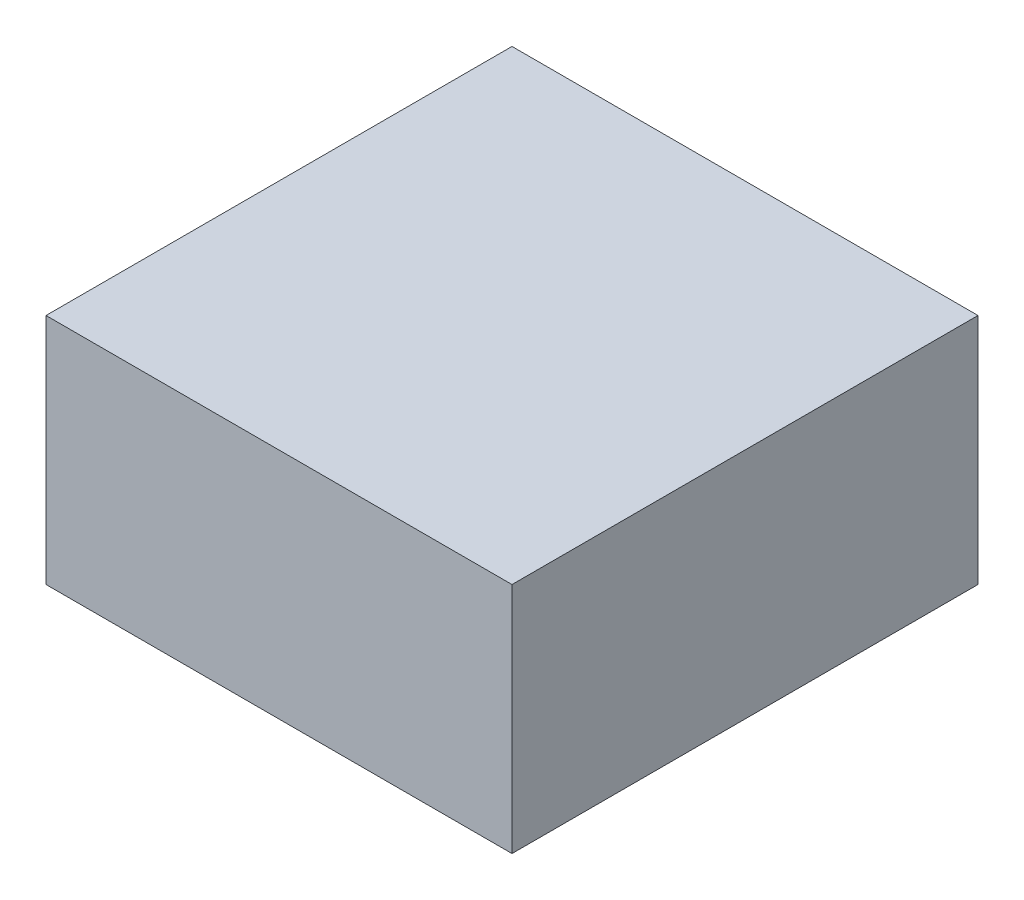
SolidWorks part; units mm, degrees
material "Beech"
ref_plane "Front Plane" through (0, 0, 0) normal (0, 0, 1) x (1, 0, 0)
ref_plane "Top Plane" through (0, 0, 0) normal (0, 1, 0) x (1, 0, 0)
ref_plane "Right Plane" through (0, 0, 0) normal (1, 0, 0) x (0, 0, -1)
sketch "Sketch1" plane through (0, 0, 0) normal (0, 1, 0) x (1, 0, 0)
  line L1 (0, 0) -> (304.8, 0)
  line L2 (0, 0) -> (0, 304.8)
  line L3 (0, 304.8) -> (304.8, 304.8)
  line L4 (304.8, 0) -> (304.8, 304.8)
  dimension "D1" = 304.8
  dimension "D2" = 304.8
extrude "Boss-Extrude1" add sketch "Sketch1" along normal blind 6.35
sketch "Sketch2" plane through (0, 6.35, 0) normal (0, 1, 0) x (1, 0, 0)
  line L1 (304.8, 304.8) -> (0, 304.8) construction
  line L2 (12.7, 304.8) -> (12.7, 292.1)
  line L3 (12.7, 292.1) -> (0, 292.1)
  line L4 (0, 304.8) -> (0, 0) construction
  line L6 (0, 292.1) -> (0, 0)
  line L7 (0, 0) -> (304.8, 0)
  line L8 (304.8, 0) -> (304.8, 304.8)
  line L9 (304.8, 304.8) -> (12.7, 304.8)
  dimension "D1" = 12.7
  dimension "D2" = 12.7
extrude "Cut-Extrude2" cut sketch "Sketch2" against normal blind 6.35 contours L3 L6 L7 L8 L9 L2
